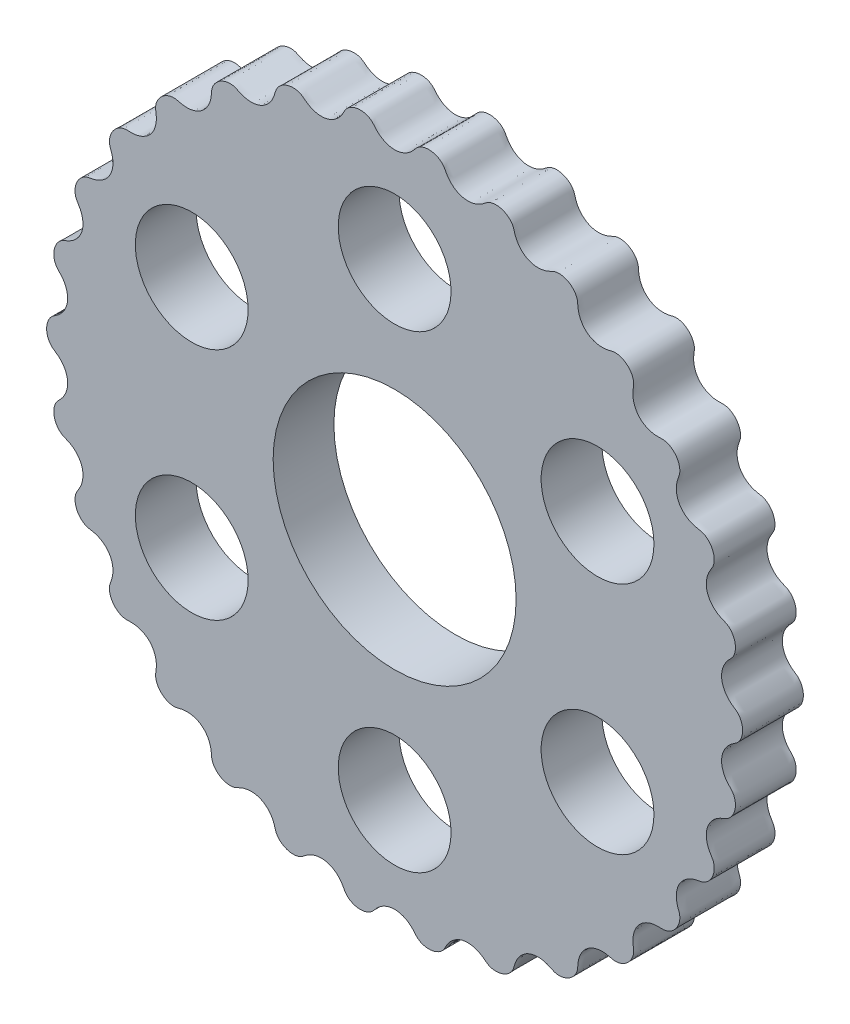
SolidWorks part; units mm, degrees
ref_plane "Front Plane" through (0, 0, 0) normal (0, 0, 1) x (1, 0, 0)
ref_plane "Top Plane" through (0, 0, 0) normal (0, 1, 0) x (1, 0, 0)
ref_plane "Right Plane" through (0, 0, 0) normal (1, 0, 0) x (0, 0, -1)
curve "Curve1"
sketch "Sketch1" plane through (0, 0, 0) normal (0, 0, 1) x (1, 0, 0)
  spline S0 degree 3 poles (1.4747, 38.2235) (0, 37.668) (-1.4747, 38.2235) (-2.1416, 38.8853) (-2.3846, 39.1801) (-2.5082, 39.3226) (-2.615, 39.4276) (-2.7406, 39.5292) (-2.9001, 39.6323) (-3.0988, 39.7306) (-3.3354, 39.8143) (-3.6035, 39.873) (-3.8933, 39.8988) (-4.1923, 39.8868) (-4.4872, 39.8364) (-4.7653, 39.7509) (-5.0154, 39.6377) (-5.2294, 39.5067) (-5.4033, 39.3692) (-5.5379, 39.2352) (-5.6396, 39.1097) (-5.7222, 38.9848) (-5.8135, 38.8197) (-5.9899, 38.4809) (-6.5047, 37.6948) (-7.8316, 36.8449) (-9.3896, 37.0816) (-10.1795, 37.5903) (-10.4785, 37.8281) (-10.6291, 37.9418) (-10.7554, 38.0223) (-10.8993, 38.0956) (-11.0767, 38.1632) (-11.2915, 38.2181) (-11.5403, 38.2508) (-11.8148, 38.2525) (-12.1036, 38.2175) (-12.3936, 38.1436) (-12.6716, 38.0329) (-12.9259, 37.8915) (-13.1469, 37.7288) (-13.329, 37.5561) (-13.4705, 37.3854) (-13.5743, 37.2264) (-13.6477, 37.0825) (-13.7025, 36.9432) (-13.7576, 36.7627) (-13.8596, 36.3946) (-14.1997, 35.5187) (-15.321, 34.4114) (-16.8941, 34.3191) (-17.7726, 34.6524) (-18.1144, 34.8229) (-18.2853, 34.9028) (-18.4256, 34.9553) (-18.5816, 34.997) (-18.7693, 35.0263) (-18.9908, 35.0353) (-19.2409, 35.0155) (-19.5098, 34.9601) (-19.785, 34.8658) (-20.0533, 34.7333) (-20.3022, 34.5672) (-20.5215, 34.376) (-20.7039, 34.1709) (-20.8461, 33.9642) (-20.949, 33.7678) (-21.0175, 33.5907) (-21.0593, 33.4347) (-21.084, 33.287) (-21.1003, 33.099) (-21.1236, 32.7177) (-21.2742, 31.7902) (-22.1407, 30.474) (-23.6602, 30.0567) (-24.5888, 30.2001) (-24.9586, 30.2957) (-25.1425, 30.3383) (-25.2906, 30.3605) (-25.4519, 30.3689) (-25.6415, 30.3585) (-25.8601, 30.3213) (-26.1006, 30.2499) (-26.3521, 30.1399) (-26.6016, 29.9904) (-26.8365, 29.8049) (-27.0455, 29.5908) (-27.2202, 29.3582) (-27.356, 29.1196) (-27.4521, 28.8878) (-27.512, 28.6743) (-27.5421, 28.4868) (-27.5506, 28.3256) (-27.544, 28.1759) (-27.5209, 27.9887) (-27.4644, 27.6109) (-27.4189, 26.6724) (-27.9928, 25.2048) (-29.3923, 24.4806) (-30.3305, 24.4278) (-30.7121, 24.4445) (-30.9007, 24.448) (-31.0502, 24.4389) (-31.2097, 24.4135) (-31.393, 24.364) (-31.5991, 24.2821) (-31.8196, 24.1623) (-32.0427, 24.0023) (-32.2557, 23.8042) (-32.4468, 23.574) (-32.6067, 23.3211) (-32.7293, 23.0572) (-32.8125, 22.7956) (-32.8583, 22.5489) (-32.8725, 22.3277) (-32.863, 22.138) (-32.8378, 21.9785) (-32.8002, 21.8335) (-32.7387, 21.6551) (-32.6049, 21.2974) (-32.3652, 20.3888) (-32.6214, 18.834) (-33.8398, 17.8346) (-34.7465, 17.588) (-35.1232, 17.5249) (-35.3085, 17.4891) (-35.4528, 17.4491) (-35.6036, 17.3912) (-35.7726, 17.3046) (-35.9571, 17.1817) (-36.1479, 17.0186) (-36.3328, 16.8158) (-36.5, 16.5777) (-36.6391, 16.3128) (-36.7429, 16.0321) (-36.808, 15.7486) (-36.8349, 15.4754) (-36.8285, 15.2246) (-36.7963, 15.0052) (-36.7476, 14.8217) (-36.6898, 14.6708) (-36.6229, 14.5368) (-36.5256, 14.3752) (-36.3204, 14.053) (-35.897, 13.2142) (-35.8244, 11.64) (-36.8084, 10.4092) (-37.644, 9.9794) (-37.9993, 9.8394) (-38.1731, 9.7659) (-38.306, 9.6967) (-38.4414, 9.6087) (-38.5887, 9.4889) (-38.7437, 9.3303) (-38.8963, 9.1312) (-39.035, 8.8943) (-39.1491, 8.6267) (-39.2301, 8.3386) (-39.2733, 8.0425) (-39.2779, 7.7516) (-39.2475, 7.4788) (-39.1891, 7.2348) (-39.112, 7.0269) (-39.0262, 6.8575) (-38.9383, 6.722) (-38.845, 6.6048) (-38.7162, 6.4669) (-38.4485, 6.1945) (-37.86, 5.462) (-37.4616, 3.9374) (-38.1683, 2.5289) (-38.8962, 1.9347) (-39.2147, 1.7239) (-39.3694, 1.6158) (-39.485, 1.5206) (-39.5991, 1.4063) (-39.7183, 1.2585) (-39.8369, 1.0712) (-39.9448, 0.8446) (-40.0313, 0.5841) (-40.0872, 0.2986) (-40.1065, 0) (-40.0872, -0.2986) (-40.0313, -0.5841) (-39.9448, -0.8446) (-39.8369, -1.0712) (-39.7183, -1.2585) (-39.5991, -1.4063) (-39.485, -1.5206) (-39.3694, -1.6158) (-39.2147, -1.7239) (-38.8962, -1.9347) (-38.1683, -2.5289) (-37.4616, -3.9374) (-37.86, -5.462) (-38.4485, -6.1945) (-38.7162, -6.4669) (-38.845, -6.6048) (-38.9383, -6.722) (-39.0262, -6.8575) (-39.112, -7.0269) (-39.1891, -7.2348) (-39.2475, -7.4788) (-39.2779, -7.7516) (-39.2733, -8.0425) (-39.2301, -8.3386) (-39.1491, -8.6267) (-39.035, -8.8943) (-38.8963, -9.1312) (-38.7437, -9.3303) (-38.5887, -9.4889) (-38.4414, -9.6087) (-38.306, -9.6967) (-38.1731, -9.7659) (-37.9993, -9.8394) (-37.644, -9.9794) (-36.8084, -10.4092) (-35.8244, -11.64) (-35.897, -13.2142) (-36.3204, -14.053) (-36.5256, -14.3752) (-36.6229, -14.5368) (-36.6898, -14.6708) (-36.7476, -14.8217) (-36.7963, -15.0052) (-36.8285, -15.2246) (-36.8349, -15.4754) (-36.808, -15.7486) (-36.7429, -16.0321) (-36.6391, -16.3128) (-36.5, -16.5777) (-36.3328, -16.8158) (-36.1479, -17.0186) (-35.9571, -17.1817) (-35.7726, -17.3046) (-35.6036, -17.3912) (-35.4528, -17.4491) (-35.3085, -17.4891) (-35.1232, -17.5249) (-34.7465, -17.588) (-33.8398, -17.8346) (-32.6214, -18.834) (-32.3652, -20.3888) (-32.6049, -21.2974) (-32.7387, -21.6551) (-32.8002, -21.8335) (-32.8378, -21.9785) (-32.863, -22.138) (-32.8725, -22.3277) (-32.8583, -22.5489) (-32.8125, -22.7956) (-32.7293, -23.0572) (-32.6067, -23.3211) (-32.4468, -23.574) (-32.2557, -23.8042) (-32.0427, -24.0023) (-31.8196, -24.1623) (-31.5991, -24.2821) (-31.393, -24.364) (-31.2097, -24.4135) (-31.0502, -24.4389) (-30.9007, -24.448) (-30.7121, -24.4445) (-30.3305, -24.4278) (-29.3923, -24.4806) (-27.9928, -25.2048) (-27.4189, -26.6724) (-27.4644, -27.6109) (-27.5209, -27.9887) (-27.544, -28.1759) (-27.5506, -28.3256) (-27.5421, -28.4868) (-27.512, -28.6743) (-27.4521, -28.8878) (-27.356, -29.1196) (-27.2202, -29.3582) (-27.0455, -29.5908) (-26.8365, -29.8049) (-26.6016, -29.9904) (-26.3521, -30.1399) (-26.1006, -30.2499) (-25.8601, -30.3213) (-25.6415, -30.3585) (-25.4519, -30.3689) (-25.2906, -30.3605) (-25.1425, -30.3383) (-24.9586, -30.2957) (-24.5888, -30.2001) (-23.6602, -30.0567) (-22.1407, -30.474) (-21.2742, -31.7902) (-21.1236, -32.7177) (-21.1003, -33.099) (-21.084, -33.287) (-21.0593, -33.4347) (-21.0175, -33.5907) (-20.949, -33.7678) (-20.8461, -33.9642) (-20.7039, -34.1709) (-20.5215, -34.376) (-20.3022, -34.5672) (-20.0533, -34.7333) (-19.785, -34.8658) (-19.5098, -34.9601) (-19.2409, -35.0155) (-18.9908, -35.0353) (-18.7693, -35.0263) (-18.5816, -34.997) (-18.4256, -34.9553) (-18.2853, -34.9028) (-18.1144, -34.8229) (-17.7726, -34.6524) (-16.8941, -34.3191) (-15.321, -34.4114) (-14.1997, -35.5187) (-13.8596, -36.3946) (-13.7576, -36.7627) (-13.7025, -36.9432) (-13.6477, -37.0825) (-13.5743, -37.2264) (-13.4705, -37.3854) (-13.329, -37.5561) (-13.1469, -37.7288) (-12.9259, -37.8915) (-12.6716, -38.0329) (-12.3936, -38.1436) (-12.1036, -38.2175) (-11.8148, -38.2525) (-11.5403, -38.2508) (-11.2915, -38.2181) (-11.0767, -38.1632) (-10.8993, -38.0956) (-10.7554, -38.0223) (-10.6291, -37.9418) (-10.4785, -37.8281) (-10.1795, -37.5903) (-9.3896, -37.0816) (-7.8316, -36.8449) (-6.5047, -37.6948) (-5.9899, -38.4809) (-5.8135, -38.8197) (-5.7222, -38.9848) (-5.6396, -39.1097) (-5.5379, -39.2352) (-5.4033, -39.3692) (-5.2294, -39.5067) (-5.0154, -39.6377) (-4.7653, -39.7509) (-4.4872, -39.8364) (-4.1923, -39.8868) (-3.8933, -39.8988) (-3.6035, -39.873) (-3.3354, -39.8143) (-3.0988, -39.7306) (-2.9001, -39.6323) (-2.7406, -39.5292) (-2.615, -39.4276) (-2.5082, -39.3226) (-2.3846, -39.1801) (-2.1416, -38.8853) (-1.4747, -38.2235) (0, -37.668) (1.4747, -38.2235) (2.1416, -38.8853) (2.3846, -39.1801) (2.5082, -39.3226) (2.615, -39.4276) (2.7406, -39.5292) (2.9001, -39.6323) (3.0988, -39.7306) (3.3354, -39.8143) (3.6035, -39.873) (3.8933, -39.8988) (4.1923, -39.8868) (4.4872, -39.8364) (4.7653, -39.7509) (5.0154, -39.6377) (5.2294, -39.5067) (5.4033, -39.3692) (5.5379, -39.2352) (5.6396, -39.1097) (5.7222, -38.9848) (5.8135, -38.8197) (5.9899, -38.4809) (6.5047, -37.6948) (7.8316, -36.8449) (9.3896, -37.0816) (10.1795, -37.5903) (10.4785, -37.8281) (10.6291, -37.9418) (10.7554, -38.0223) (10.8993, -38.0956) (11.0767, -38.1632) (11.2915, -38.2181) (11.5403, -38.2508) (11.8148, -38.2525) (12.1036, -38.2175) (12.3936, -38.1436) (12.6716, -38.0329) (12.9259, -37.8915) (13.1469, -37.7288) (13.329, -37.5561) (13.4705, -37.3854) (13.5743, -37.2264) (13.6477, -37.0825) (13.7025, -36.9432) (13.7576, -36.7627) (13.8596, -36.3946) (14.1997, -35.5187) (15.321, -34.4114) (16.8941, -34.3191) (17.7726, -34.6524) (18.1144, -34.8229) (18.2853, -34.9028) (18.4256, -34.9553) (18.5816, -34.997) (18.7693, -35.0263) (18.9908, -35.0353) (19.2409, -35.0155) (19.5098, -34.9601) (19.785, -34.8658) (20.0533, -34.7333) (20.3022, -34.5672) (20.5215, -34.376) (20.7039, -34.1709) (20.8461, -33.9642) (20.949, -33.7678) (21.0175, -33.5907) (21.0593, -33.4347) (21.084, -33.287) (21.1003, -33.099) (21.1236, -32.7177) (21.2742, -31.7902) (22.1407, -30.474) (23.6602, -30.0567) (24.5888, -30.2001) (24.9586, -30.2957) (25.1425, -30.3383) (25.2906, -30.3605) (25.4519, -30.3689) (25.6415, -30.3585) (25.8601, -30.3213) (26.1006, -30.2499) (26.3521, -30.1399) (26.6016, -29.9904) (26.8365, -29.8049) (27.0455, -29.5908) (27.2202, -29.3582) (27.356, -29.1196) (27.4521, -28.8878) (27.512, -28.6743) (27.5421, -28.4868) (27.5506, -28.3256) (27.544, -28.1759) (27.5209, -27.9887) (27.4644, -27.6109) (27.4189, -26.6724) (27.9928, -25.2048) (29.3923, -24.4806) (30.3305, -24.4278) (30.7121, -24.4445) (30.9007, -24.448) (31.0502, -24.4389) (31.2097, -24.4135) (31.393, -24.364) (31.5991, -24.2821) (31.8196, -24.1623) (32.0427, -24.0023) (32.2557, -23.8042) (32.4468, -23.574) (32.6067, -23.3211) (32.7293, -23.0572) (32.8125, -22.7956) (32.8583, -22.5489) (32.8725, -22.3277) (32.863, -22.138) (32.8378, -21.9785) (32.8002, -21.8335) (32.7387, -21.6551) (32.6049, -21.2974) (32.3652, -20.3888) (32.6214, -18.834) (33.8398, -17.8346) (34.7465, -17.588) (35.1232, -17.5249) (35.3085, -17.4891) (35.4528, -17.4491) (35.6036, -17.3912) (35.7726, -17.3046) (35.9571, -17.1817) (36.1479, -17.0186) (36.3328, -16.8158) (36.5, -16.5777) (36.6391, -16.3128) (36.7429, -16.0321) (36.808, -15.7486) (36.8349, -15.4754) (36.8285, -15.2246) (36.7963, -15.0052) (36.7476, -14.8217) (36.6898, -14.6708) (36.6229, -14.5368) (36.5256, -14.3752) (36.3204, -14.053) (35.897, -13.2142) (35.8244, -11.64) (36.8084, -10.4092) (37.644, -9.9794) (37.9993, -9.8394) (38.1731, -9.7659) (38.306, -9.6967) (38.4414, -9.6087) (38.5887, -9.4889) (38.7437, -9.3303) (38.8963, -9.1312) (39.035, -8.8943) (39.1491, -8.6267) (39.2301, -8.3386) (39.2733, -8.0425) (39.2779, -7.7516) (39.2475, -7.4788) (39.1891, -7.2348) (39.112, -7.0269) (39.0262, -6.8575) (38.9383, -6.722) (38.845, -6.6048) (38.7162, -6.4669) (38.4485, -6.1945) (37.86, -5.462) (37.4616, -3.9374) (38.1683, -2.5289) (38.8962, -1.9347) (39.2147, -1.7239) (39.3694, -1.6158) (39.485, -1.5206) (39.5991, -1.4063) (39.7183, -1.2585) (39.8369, -1.0712) (39.9448, -0.8446) (40.0313, -0.5841) (40.0872, -0.2986) (40.1065, 0) (40.0872, 0.2986) (40.0313, 0.5841) (39.9448, 0.8446) (39.8369, 1.0712) (39.7183, 1.2585) (39.5991, 1.4063) (39.485, 1.5206) (39.3694, 1.6158) (39.2147, 1.7239) (38.8962, 1.9347) (38.1683, 2.5289) (37.4616, 3.9374) (37.86, 5.462) (38.4485, 6.1945) (38.7162, 6.4669) (38.845, 6.6048) (38.9383, 6.722) (39.0262, 6.8575) (39.112, 7.0269) (39.1891, 7.2348) (39.2475, 7.4788) (39.2779, 7.7516) (39.2733, 8.0425) (39.2301, 8.3386) (39.1491, 8.6267) (39.035, 8.8943) (38.8963, 9.1312) (38.7437, 9.3303) (38.5887, 9.4889) (38.4414, 9.6087) (38.306, 9.6967) (38.1731, 9.7659) (37.9993, 9.8394) (37.644, 9.9794) (36.8084, 10.4092) (35.8244, 11.64) (35.897, 13.2142) (36.3204, 14.053) (36.5256, 14.3752) (36.6229, 14.5368) (36.6898, 14.6708) (36.7476, 14.8217) (36.7963, 15.0052) (36.8285, 15.2246) (36.8349, 15.4754) (36.808, 15.7486) (36.7429, 16.0321) (36.6391, 16.3128) (36.5, 16.5777) (36.3328, 16.8158) (36.1479, 17.0186) (35.9571, 17.1817) (35.7726, 17.3046) (35.6036, 17.3912) (35.4528, 17.4491) (35.3085, 17.4891) (35.1232, 17.5249) (34.7465, 17.588) (33.8398, 17.8346) (32.6214, 18.834) (32.3652, 20.3888) (32.6049, 21.2974) (32.7387, 21.6551) (32.8002, 21.8335) (32.8378, 21.9785) (32.863, 22.138) (32.8725, 22.3277) (32.8583, 22.5489) (32.8125, 22.7956) (32.7293, 23.0572) (32.6067, 23.3211) (32.4468, 23.574) (32.2557, 23.8042) (32.0427, 24.0023) (31.8196, 24.1623) (31.5991, 24.2821) (31.393, 24.364) (31.2097, 24.4135) (31.0502, 24.4389) (30.9007, 24.448) (30.7121, 24.4445) (30.3305, 24.4278) (29.3923, 24.4806) (27.9928, 25.2048) (27.4189, 26.6724) (27.4644, 27.6109) (27.5209, 27.9887) (27.544, 28.1759) (27.5506, 28.3256) (27.5421, 28.4868) (27.512, 28.6743) (27.4521, 28.8878) (27.356, 29.1196) (27.2202, 29.3582) (27.0455, 29.5908) (26.8365, 29.8049) (26.6016, 29.9904) (26.3521, 30.1399) (26.1006, 30.2499) (25.8601, 30.3213) (25.6415, 30.3585) (25.4519, 30.3689) (25.2906, 30.3605) (25.1425, 30.3383) (24.9586, 30.2957) (24.5888, 30.2001) (23.6602, 30.0567) (22.1407, 30.474) (21.2742, 31.7902) (21.1236, 32.7177) (21.1003, 33.099) (21.084, 33.287) (21.0593, 33.4347) (21.0175, 33.5907) (20.949, 33.7678) (20.8461, 33.9642) (20.7039, 34.1709) (20.5215, 34.376) (20.3022, 34.5672) (20.0533, 34.7333) (19.785, 34.8658) (19.5098, 34.9601) (19.2409, 35.0155) (18.9908, 35.0353) (18.7693, 35.0263) (18.5816, 34.997) (18.4256, 34.9553) (18.2853, 34.9028) (18.1144, 34.8229) (17.7726, 34.6524) (16.8941, 34.3191) (15.321, 34.4114) (14.1997, 35.5187) (13.8596, 36.3946) (13.7576, 36.7627) (13.7025, 36.9432) (13.6477, 37.0825) (13.5743, 37.2264) (13.4705, 37.3854) (13.329, 37.5561) (13.1469, 37.7288) (12.9259, 37.8915) (12.6716, 38.0329) (12.3936, 38.1436) (12.1036, 38.2175) (11.8148, 38.2525) (11.5403, 38.2508) (11.2915, 38.2181) (11.0767, 38.1632) (10.8993, 38.0956) (10.7554, 38.0223) (10.6291, 37.9418) (10.4785, 37.8281) (10.1795, 37.5903) (9.3896, 37.0816) (7.8316, 36.8449) (6.5047, 37.6948) (5.9899, 38.4809) (5.8135, 38.8197) (5.7222, 38.9848) (5.6396, 39.1097) (5.5379, 39.2352) (5.4033, 39.3692) (5.2294, 39.5067) (5.0154, 39.6377) (4.7653, 39.7509) (4.4872, 39.8364) (4.1923, 39.8868) (3.8933, 39.8988) (3.6035, 39.873) (3.3354, 39.8143) (3.0988, 39.7306) (2.9001, 39.6323) (2.7406, 39.5292) (2.615, 39.4276) (2.5082, 39.3226) (2.3846, 39.1801) (2.1416, 38.8853) (1.4747, 38.2235) (0, 37.668) (-1.4747, 38.2235) knots -0.009773 -0.008819 -0.006325 0 0.006325 0.008819 0.009773 0.010309 0.010787 0.011333 0.01199 0.012763 0.013641 0.014601 0.015619 0.016667 0.017714 0.018732 0.019693 0.02057 0.021343 0.022 0.022547 0.023025 0.02356 0.024514 0.027009 0.033333 0.039658 0.042152 0.043106 0.043642 0.04412 0.044667 0.045324 0.046097 0.046974 0.047935 0.048953 0.05 0.051047 0.052065 0.053026 0.053903 0.054676 0.055333 0.05588 0.056358 0.056894 0.057848 0.060342 0.066667 0.072991 0.075486 0.07644 0.076975 0.077453 0.078 0.078657 0.07943 0.080307 0.081268 0.082286 0.083333 0.084381 0.085399 0.086359 0.087237 0.08801 0.088667 0.089213 0.089691 0.090227 0.091181 0.093675 0.1 0.106325 0.108819 0.109773 0.110309 0.110787 0.111333 0.11199 0.112763 0.113641 0.114601 0.115619 0.116667 0.117714 0.118732 0.119693 0.12057 0.121343 0.122 0.122547 0.123025 0.12356 0.124514 0.127009 0.133333 0.139658 0.142152 0.143106 0.143642 0.14412 0.144667 0.145324 0.146097 0.146974 0.147935 0.148953 0.15 0.151047 0.152065 0.153026 0.153903 0.154676 0.155333 0.15588 0.156358 0.156894 0.157848 0.160342 0.166667 0.172991 0.175486 0.17644 0.176975 0.177453 0.178 0.178657 0.17943 0.180307 0.181268 0.182286 0.183333 0.184381 0.185399 0.186359 0.187237 0.18801 0.188667 0.189213 0.189691 0.190227 0.191181 0.193675 0.2 0.206325 0.208819 0.209773 0.210309 0.210787 0.211333 0.21199 0.212763 0.213641 0.214601 0.215619 0.216667 0.217714 0.218732 0.219693 0.22057 0.221343 0.222 0.222547 0.223025 0.22356 0.224514 0.227009 0.233333 0.239658 0.242152 0.243106 0.243642 0.24412 0.244667 0.245324 0.246097 0.246974 0.247935 0.248953 0.25 0.251047 0.252065 0.253026 0.253903 0.254676 0.255333 0.25588 0.256358 0.256894 0.257848 0.260342 0.266667 0.272991 0.275486 0.27644 0.276975 0.277453 0.278 0.278657 0.27943 0.280307 0.281268 0.282286 0.283333 0.284381 0.285399 0.286359 0.287237 0.28801 0.288667 0.289213 0.289691 0.290227 0.291181 0.293675 0.3 0.306325 0.308819 0.309773 0.310309 0.310787 0.311333 0.31199 0.312763 0.313641 0.314601 0.315619 0.316667 0.317714 0.318732 0.319693 0.32057 0.321343 0.322 0.322547 0.323025 0.32356 0.324514 0.327009 0.333333 0.339658 0.342152 0.343106 0.343642 0.34412 0.344667 0.345324 0.346097 0.346974 0.347935 0.348953 0.35 0.351047 0.352065 0.353026 0.353903 0.354676 0.355333 0.35588 0.356358 0.356894 0.357848 0.360342 0.366667 0.372991 0.375486 0.37644 0.376975 0.377453 0.378 0.378657 0.37943 0.380307 0.381268 0.382286 0.383333 0.384381 0.385399 0.386359 0.387237 0.38801 0.388667 0.389213 0.389691 0.390227 0.391181 0.393675 0.4 0.406325 0.408819 0.409773 0.410309 0.410787 0.411333 0.41199 0.412763 0.413641 0.414601 0.415619 0.416667 0.417714 0.418732 0.419693 0.42057 0.421343 0.422 0.422547 0.423025 0.42356 0.424514 0.427009 0.433333 0.439658 0.442152 0.443106 0.443642 0.44412 0.444667 0.445324 0.446097 0.446974 0.447935 0.448953 0.45 0.451047 0.452065 0.453026 0.453903 0.454676 0.455333 0.45588 0.456358 0.456894 0.457848 0.460342 0.466667 0.472991 0.475486 0.47644 0.476975 0.477453 0.478 0.478657 0.47943 0.480307 0.481268 0.482286 0.483333 0.484381 0.485399 0.486359 0.487237 0.48801 0.488667 0.489213 0.489691 0.490227 0.491181 0.493675 0.5 0.506325 0.508819 0.509773 0.510309 0.510787 0.511333 0.51199 0.512763 0.513641 0.514601 0.515619 0.516667 0.517714 0.518732 0.519693 0.52057 0.521343 0.522 0.522547 0.523025 0.52356 0.524514 0.527009 0.533333 0.539658 0.542152 0.543106 0.543642 0.54412 0.544667 0.545324 0.546097 0.546974 0.547935 0.548953 0.55 0.551047 0.552065 0.553026 0.553903 0.554676 0.555333 0.55588 0.556358 0.556894 0.557848 0.560342 0.566667 0.572991 0.575486 0.57644 0.576975 0.577453 0.578 0.578657 0.57943 0.580307 0.581268 0.582286 0.583333 0.584381 0.585399 0.586359 0.587237 0.58801 0.588667 0.589213 0.589691 0.590227 0.591181 0.593675 0.6 0.606325 0.608819 0.609773 0.610309 0.610787 0.611333 0.61199 0.612763 0.613641 0.614601 0.615619 0.616667 0.617714 0.618732 0.619693 0.62057 0.621343 0.622 0.622547 0.623025 0.62356 0.624514 0.627009 0.633333 0.639658 0.642152 0.643106 0.643642 0.64412 0.644667 0.645324 0.646097 0.646974 0.647935 0.648953 0.65 0.651047 0.652065 0.653026 0.653903 0.654676 0.655333 0.65588 0.656358 0.656894 0.657848 0.660342 0.666667 0.672991 0.675486 0.67644 0.676975 0.677453 0.678 0.678657 0.67943 0.680307 0.681268 0.682286 0.683333 0.684381 0.685399 0.686359 0.687237 0.68801 0.688667 0.689213 0.689691 0.690227 0.691181 0.693675 0.7 0.706325 0.708819 0.709773 0.710309 0.710787 0.711333 0.71199 0.712763 0.713641 0.714601 0.715619 0.716667 0.717714 0.718732 0.719693 0.72057 0.721343 0.722 0.722547 0.723025 0.72356 0.724514 0.727009 0.733333 0.739658 0.742152 0.743106 0.743642 0.74412 0.744667 0.745324 0.746097 0.746974 0.747935 0.748953 0.75 0.751047 0.752065 0.753026 0.753903 0.754676 0.755333 0.75588 0.756358 0.756894 0.757848 0.760342 0.766667 0.772991 0.775486 0.77644 0.776975 0.777453 0.778 0.778657 0.77943 0.780307 0.781268 0.782286 0.783333 0.784381 0.785399 0.786359 0.787237 0.78801 0.788667 0.789213 0.789691 0.790227 0.791181 0.793675 0.8 0.806325 0.808819 0.809773 0.810309 0.810787 0.811333 0.81199 0.812763 0.813641 0.814601 0.815619 0.816667 0.817714 0.818732 0.819693 0.82057 0.821343 0.822 0.822547 0.823025 0.82356 0.824514 0.827009 0.833333 0.839658 0.842152 0.843106 0.843642 0.84412 0.844667 0.845324 0.846097 0.846974 0.847935 0.848953 0.85 0.851047 0.852065 0.853026 0.853903 0.854676 0.855333 0.85588 0.856358 0.856894 0.857848 0.860342 0.866667 0.872991 0.875486 0.87644 0.876975 0.877453 0.878 0.878657 0.87943 0.880307 0.881268 0.882286 0.883333 0.884381 0.885399 0.886359 0.887237 0.88801 0.888667 0.889213 0.889691 0.890227 0.891181 0.893675 0.9 0.906325 0.908819 0.909773 0.910309 0.910787 0.911333 0.91199 0.912763 0.913641 0.914601 0.915619 0.916667 0.917714 0.918732 0.919693 0.92057 0.921343 0.922 0.922547 0.923025 0.92356 0.924514 0.927009 0.933333 0.939658 0.942152 0.943106 0.943642 0.94412 0.944667 0.945324 0.946097 0.946974 0.947935 0.948953 0.95 0.951047 0.952065 0.953026 0.953903 0.954676 0.955333 0.95588 0.956358 0.956894 0.957848 0.960342 0.966667 0.972991 0.975486 0.97644 0.976975 0.977453 0.978 0.978657 0.97943 0.980307 0.981268 0.982286 0.983333 0.984381 0.985399 0.986359 0.987237 0.98801 0.988667 0.989213 0.989691 0.990227 0.991181 0.993675 1 1.006325 1.008819 1.009773 only from (0, 37.9) to (0, 37.9) construction
  spline S1 degree 3 poles (1.4747, 38.2235) (0, 37.668) (-1.4747, 38.2235) (-2.1416, 38.8853) (-2.3846, 39.1801) (-2.5082, 39.3226) (-2.615, 39.4276) (-2.7406, 39.5292) (-2.9001, 39.6323) (-3.0988, 39.7306) (-3.3354, 39.8143) (-3.6035, 39.873) (-3.8933, 39.8988) (-4.1923, 39.8868) (-4.4872, 39.8364) (-4.7653, 39.7509) (-5.0154, 39.6377) (-5.2294, 39.5067) (-5.4033, 39.3692) (-5.5379, 39.2352) (-5.6396, 39.1097) (-5.7222, 38.9848) (-5.8135, 38.8197) (-5.9899, 38.4809) (-6.5047, 37.6948) (-7.8316, 36.8449) (-9.3896, 37.0816) (-10.1795, 37.5903) (-10.4785, 37.8281) (-10.6291, 37.9418) (-10.7554, 38.0223) (-10.8993, 38.0956) (-11.0767, 38.1632) (-11.2915, 38.2181) (-11.5403, 38.2508) (-11.8148, 38.2525) (-12.1036, 38.2175) (-12.3936, 38.1436) (-12.6716, 38.0329) (-12.9259, 37.8915) (-13.1469, 37.7288) (-13.329, 37.5561) (-13.4705, 37.3854) (-13.5743, 37.2264) (-13.6477, 37.0825) (-13.7025, 36.9432) (-13.7576, 36.7627) (-13.8596, 36.3946) (-14.1997, 35.5187) (-15.321, 34.4114) (-16.8941, 34.3191) (-17.7726, 34.6524) (-18.1144, 34.8229) (-18.2853, 34.9028) (-18.4256, 34.9553) (-18.5816, 34.997) (-18.7693, 35.0263) (-18.9908, 35.0353) (-19.2409, 35.0155) (-19.5098, 34.9601) (-19.785, 34.8658) (-20.0533, 34.7333) (-20.3022, 34.5672) (-20.5215, 34.376) (-20.7039, 34.1709) (-20.8461, 33.9642) (-20.949, 33.7678) (-21.0175, 33.5907) (-21.0593, 33.4347) (-21.084, 33.287) (-21.1003, 33.099) (-21.1236, 32.7177) (-21.2742, 31.7902) (-22.1407, 30.474) (-23.6602, 30.0567) (-24.5888, 30.2001) (-24.9586, 30.2957) (-25.1425, 30.3383) (-25.2906, 30.3605) (-25.4519, 30.3689) (-25.6415, 30.3585) (-25.8601, 30.3213) (-26.1006, 30.2499) (-26.3521, 30.1399) (-26.6016, 29.9904) (-26.8365, 29.8049) (-27.0455, 29.5908) (-27.2202, 29.3582) (-27.356, 29.1196) (-27.4521, 28.8878) (-27.512, 28.6743) (-27.5421, 28.4868) (-27.5506, 28.3256) (-27.544, 28.1759) (-27.5209, 27.9887) (-27.4644, 27.6109) (-27.4189, 26.6724) (-27.9928, 25.2048) (-29.3923, 24.4806) (-30.3305, 24.4278) (-30.7121, 24.4445) (-30.9007, 24.448) (-31.0502, 24.4389) (-31.2097, 24.4135) (-31.393, 24.364) (-31.5991, 24.2821) (-31.8196, 24.1623) (-32.0427, 24.0023) (-32.2557, 23.8042) (-32.4468, 23.574) (-32.6067, 23.3211) (-32.7293, 23.0572) (-32.8125, 22.7956) (-32.8583, 22.5489) (-32.8725, 22.3277) (-32.863, 22.138) (-32.8378, 21.9785) (-32.8002, 21.8335) (-32.7387, 21.6551) (-32.6049, 21.2974) (-32.3652, 20.3888) (-32.6214, 18.834) (-33.8398, 17.8346) (-34.7465, 17.588) (-35.1232, 17.5249) (-35.3085, 17.4891) (-35.4528, 17.4491) (-35.6036, 17.3912) (-35.7726, 17.3046) (-35.9571, 17.1817) (-36.1479, 17.0186) (-36.3328, 16.8158) (-36.5, 16.5777) (-36.6391, 16.3128) (-36.7429, 16.0321) (-36.808, 15.7486) (-36.8349, 15.4754) (-36.8285, 15.2246) (-36.7963, 15.0052) (-36.7476, 14.8217) (-36.6898, 14.6708) (-36.6229, 14.5368) (-36.5256, 14.3752) (-36.3204, 14.053) (-35.897, 13.2142) (-35.8244, 11.64) (-36.8084, 10.4092) (-37.644, 9.9794) (-37.9993, 9.8394) (-38.1731, 9.7659) (-38.306, 9.6967) (-38.4414, 9.6087) (-38.5887, 9.4889) (-38.7437, 9.3303) (-38.8963, 9.1312) (-39.035, 8.8943) (-39.1491, 8.6267) (-39.2301, 8.3386) (-39.2733, 8.0425) (-39.2779, 7.7516) (-39.2475, 7.4788) (-39.1891, 7.2348) (-39.112, 7.0269) (-39.0262, 6.8575) (-38.9383, 6.722) (-38.845, 6.6048) (-38.7162, 6.4669) (-38.4485, 6.1945) (-37.86, 5.462) (-37.4616, 3.9374) (-38.1683, 2.5289) (-38.8962, 1.9347) (-39.2147, 1.7239) (-39.3694, 1.6158) (-39.485, 1.5206) (-39.5991, 1.4063) (-39.7183, 1.2585) (-39.8369, 1.0712) (-39.9448, 0.8446) (-40.0313, 0.5841) (-40.0872, 0.2986) (-40.1065, 0) (-40.0872, -0.2986) (-40.0313, -0.5841) (-39.9448, -0.8446) (-39.8369, -1.0712) (-39.7183, -1.2585) (-39.5991, -1.4063) (-39.485, -1.5206) (-39.3694, -1.6158) (-39.2147, -1.7239) (-38.8962, -1.9347) (-38.1683, -2.5289) (-37.4616, -3.9374) (-37.86, -5.462) (-38.4485, -6.1945) (-38.7162, -6.4669) (-38.845, -6.6048) (-38.9383, -6.722) (-39.0262, -6.8575) (-39.112, -7.0269) (-39.1891, -7.2348) (-39.2475, -7.4788) (-39.2779, -7.7516) (-39.2733, -8.0425) (-39.2301, -8.3386) (-39.1491, -8.6267) (-39.035, -8.8943) (-38.8963, -9.1312) (-38.7437, -9.3303) (-38.5887, -9.4889) (-38.4414, -9.6087) (-38.306, -9.6967) (-38.1731, -9.7659) (-37.9993, -9.8394) (-37.644, -9.9794) (-36.8084, -10.4092) (-35.8244, -11.64) (-35.897, -13.2142) (-36.3204, -14.053) (-36.5256, -14.3752) (-36.6229, -14.5368) (-36.6898, -14.6708) (-36.7476, -14.8217) (-36.7963, -15.0052) (-36.8285, -15.2246) (-36.8349, -15.4754) (-36.808, -15.7486) (-36.7429, -16.0321) (-36.6391, -16.3128) (-36.5, -16.5777) (-36.3328, -16.8158) (-36.1479, -17.0186) (-35.9571, -17.1817) (-35.7726, -17.3046) (-35.6036, -17.3912) (-35.4528, -17.4491) (-35.3085, -17.4891) (-35.1232, -17.5249) (-34.7465, -17.588) (-33.8398, -17.8346) (-32.6214, -18.834) (-32.3652, -20.3888) (-32.6049, -21.2974) (-32.7387, -21.6551) (-32.8002, -21.8335) (-32.8378, -21.9785) (-32.863, -22.138) (-32.8725, -22.3277) (-32.8583, -22.5489) (-32.8125, -22.7956) (-32.7293, -23.0572) (-32.6067, -23.3211) (-32.4468, -23.574) (-32.2557, -23.8042) (-32.0427, -24.0023) (-31.8196, -24.1623) (-31.5991, -24.2821) (-31.393, -24.364) (-31.2097, -24.4135) (-31.0502, -24.4389) (-30.9007, -24.448) (-30.7121, -24.4445) (-30.3305, -24.4278) (-29.3923, -24.4806) (-27.9928, -25.2048) (-27.4189, -26.6724) (-27.4644, -27.6109) (-27.5209, -27.9887) (-27.544, -28.1759) (-27.5506, -28.3256) (-27.5421, -28.4868) (-27.512, -28.6743) (-27.4521, -28.8878) (-27.356, -29.1196) (-27.2202, -29.3582) (-27.0455, -29.5908) (-26.8365, -29.8049) (-26.6016, -29.9904) (-26.3521, -30.1399) (-26.1006, -30.2499) (-25.8601, -30.3213) (-25.6415, -30.3585) (-25.4519, -30.3689) (-25.2906, -30.3605) (-25.1425, -30.3383) (-24.9586, -30.2957) (-24.5888, -30.2001) (-23.6602, -30.0567) (-22.1407, -30.474) (-21.2742, -31.7902) (-21.1236, -32.7177) (-21.1003, -33.099) (-21.084, -33.287) (-21.0593, -33.4347) (-21.0175, -33.5907) (-20.949, -33.7678) (-20.8461, -33.9642) (-20.7039, -34.1709) (-20.5215, -34.376) (-20.3022, -34.5672) (-20.0533, -34.7333) (-19.785, -34.8658) (-19.5098, -34.9601) (-19.2409, -35.0155) (-18.9908, -35.0353) (-18.7693, -35.0263) (-18.5816, -34.997) (-18.4256, -34.9553) (-18.2853, -34.9028) (-18.1144, -34.8229) (-17.7726, -34.6524) (-16.8941, -34.3191) (-15.321, -34.4114) (-14.1997, -35.5187) (-13.8596, -36.3946) (-13.7576, -36.7627) (-13.7025, -36.9432) (-13.6477, -37.0825) (-13.5743, -37.2264) (-13.4705, -37.3854) (-13.329, -37.5561) (-13.1469, -37.7288) (-12.9259, -37.8915) (-12.6716, -38.0329) (-12.3936, -38.1436) (-12.1036, -38.2175) (-11.8148, -38.2525) (-11.5403, -38.2508) (-11.2915, -38.2181) (-11.0767, -38.1632) (-10.8993, -38.0956) (-10.7554, -38.0223) (-10.6291, -37.9418) (-10.4785, -37.8281) (-10.1795, -37.5903) (-9.3896, -37.0816) (-7.8316, -36.8449) (-6.5047, -37.6948) (-5.9899, -38.4809) (-5.8135, -38.8197) (-5.7222, -38.9848) (-5.6396, -39.1097) (-5.5379, -39.2352) (-5.4033, -39.3692) (-5.2294, -39.5067) (-5.0154, -39.6377) (-4.7653, -39.7509) (-4.4872, -39.8364) (-4.1923, -39.8868) (-3.8933, -39.8988) (-3.6035, -39.873) (-3.3354, -39.8143) (-3.0988, -39.7306) (-2.9001, -39.6323) (-2.7406, -39.5292) (-2.615, -39.4276) (-2.5082, -39.3226) (-2.3846, -39.1801) (-2.1416, -38.8853) (-1.4747, -38.2235) (0, -37.668) (1.4747, -38.2235) (2.1416, -38.8853) (2.3846, -39.1801) (2.5082, -39.3226) (2.615, -39.4276) (2.7406, -39.5292) (2.9001, -39.6323) (3.0988, -39.7306) (3.3354, -39.8143) (3.6035, -39.873) (3.8933, -39.8988) (4.1923, -39.8868) (4.4872, -39.8364) (4.7653, -39.7509) (5.0154, -39.6377) (5.2294, -39.5067) (5.4033, -39.3692) (5.5379, -39.2352) (5.6396, -39.1097) (5.7222, -38.9848) (5.8135, -38.8197) (5.9899, -38.4809) (6.5047, -37.6948) (7.8316, -36.8449) (9.3896, -37.0816) (10.1795, -37.5903) (10.4785, -37.8281) (10.6291, -37.9418) (10.7554, -38.0223) (10.8993, -38.0956) (11.0767, -38.1632) (11.2915, -38.2181) (11.5403, -38.2508) (11.8148, -38.2525) (12.1036, -38.2175) (12.3936, -38.1436) (12.6716, -38.0329) (12.9259, -37.8915) (13.1469, -37.7288) (13.329, -37.5561) (13.4705, -37.3854) (13.5743, -37.2264) (13.6477, -37.0825) (13.7025, -36.9432) (13.7576, -36.7627) (13.8596, -36.3946) (14.1997, -35.5187) (15.321, -34.4114) (16.8941, -34.3191) (17.7726, -34.6524) (18.1144, -34.8229) (18.2853, -34.9028) (18.4256, -34.9553) (18.5816, -34.997) (18.7693, -35.0263) (18.9908, -35.0353) (19.2409, -35.0155) (19.5098, -34.9601) (19.785, -34.8658) (20.0533, -34.7333) (20.3022, -34.5672) (20.5215, -34.376) (20.7039, -34.1709) (20.8461, -33.9642) (20.949, -33.7678) (21.0175, -33.5907) (21.0593, -33.4347) (21.084, -33.287) (21.1003, -33.099) (21.1236, -32.7177) (21.2742, -31.7902) (22.1407, -30.474) (23.6602, -30.0567) (24.5888, -30.2001) (24.9586, -30.2957) (25.1425, -30.3383) (25.2906, -30.3605) (25.4519, -30.3689) (25.6415, -30.3585) (25.8601, -30.3213) (26.1006, -30.2499) (26.3521, -30.1399) (26.6016, -29.9904) (26.8365, -29.8049) (27.0455, -29.5908) (27.2202, -29.3582) (27.356, -29.1196) (27.4521, -28.8878) (27.512, -28.6743) (27.5421, -28.4868) (27.5506, -28.3256) (27.544, -28.1759) (27.5209, -27.9887) (27.4644, -27.6109) (27.4189, -26.6724) (27.9928, -25.2048) (29.3923, -24.4806) (30.3305, -24.4278) (30.7121, -24.4445) (30.9007, -24.448) (31.0502, -24.4389) (31.2097, -24.4135) (31.393, -24.364) (31.5991, -24.2821) (31.8196, -24.1623) (32.0427, -24.0023) (32.2557, -23.8042) (32.4468, -23.574) (32.6067, -23.3211) (32.7293, -23.0572) (32.8125, -22.7956) (32.8583, -22.5489) (32.8725, -22.3277) (32.863, -22.138) (32.8378, -21.9785) (32.8002, -21.8335) (32.7387, -21.6551) (32.6049, -21.2974) (32.3652, -20.3888) (32.6214, -18.834) (33.8398, -17.8346) (34.7465, -17.588) (35.1232, -17.5249) (35.3085, -17.4891) (35.4528, -17.4491) (35.6036, -17.3912) (35.7726, -17.3046) (35.9571, -17.1817) (36.1479, -17.0186) (36.3328, -16.8158) (36.5, -16.5777) (36.6391, -16.3128) (36.7429, -16.0321) (36.808, -15.7486) (36.8349, -15.4754) (36.8285, -15.2246) (36.7963, -15.0052) (36.7476, -14.8217) (36.6898, -14.6708) (36.6229, -14.5368) (36.5256, -14.3752) (36.3204, -14.053) (35.897, -13.2142) (35.8244, -11.64) (36.8084, -10.4092) (37.644, -9.9794) (37.9993, -9.8394) (38.1731, -9.7659) (38.306, -9.6967) (38.4414, -9.6087) (38.5887, -9.4889) (38.7437, -9.3303) (38.8963, -9.1312) (39.035, -8.8943) (39.1491, -8.6267) (39.2301, -8.3386) (39.2733, -8.0425) (39.2779, -7.7516) (39.2475, -7.4788) (39.1891, -7.2348) (39.112, -7.0269) (39.0262, -6.8575) (38.9383, -6.722) (38.845, -6.6048) (38.7162, -6.4669) (38.4485, -6.1945) (37.86, -5.462) (37.4616, -3.9374) (38.1683, -2.5289) (38.8962, -1.9347) (39.2147, -1.7239) (39.3694, -1.6158) (39.485, -1.5206) (39.5991, -1.4063) (39.7183, -1.2585) (39.8369, -1.0712) (39.9448, -0.8446) (40.0313, -0.5841) (40.0872, -0.2986) (40.1065, 0) (40.0872, 0.2986) (40.0313, 0.5841) (39.9448, 0.8446) (39.8369, 1.0712) (39.7183, 1.2585) (39.5991, 1.4063) (39.485, 1.5206) (39.3694, 1.6158) (39.2147, 1.7239) (38.8962, 1.9347) (38.1683, 2.5289) (37.4616, 3.9374) (37.86, 5.462) (38.4485, 6.1945) (38.7162, 6.4669) (38.845, 6.6048) (38.9383, 6.722) (39.0262, 6.8575) (39.112, 7.0269) (39.1891, 7.2348) (39.2475, 7.4788) (39.2779, 7.7516) (39.2733, 8.0425) (39.2301, 8.3386) (39.1491, 8.6267) (39.035, 8.8943) (38.8963, 9.1312) (38.7437, 9.3303) (38.5887, 9.4889) (38.4414, 9.6087) (38.306, 9.6967) (38.1731, 9.7659) (37.9993, 9.8394) (37.644, 9.9794) (36.8084, 10.4092) (35.8244, 11.64) (35.897, 13.2142) (36.3204, 14.053) (36.5256, 14.3752) (36.6229, 14.5368) (36.6898, 14.6708) (36.7476, 14.8217) (36.7963, 15.0052) (36.8285, 15.2246) (36.8349, 15.4754) (36.808, 15.7486) (36.7429, 16.0321) (36.6391, 16.3128) (36.5, 16.5777) (36.3328, 16.8158) (36.1479, 17.0186) (35.9571, 17.1817) (35.7726, 17.3046) (35.6036, 17.3912) (35.4528, 17.4491) (35.3085, 17.4891) (35.1232, 17.5249) (34.7465, 17.588) (33.8398, 17.8346) (32.6214, 18.834) (32.3652, 20.3888) (32.6049, 21.2974) (32.7387, 21.6551) (32.8002, 21.8335) (32.8378, 21.9785) (32.863, 22.138) (32.8725, 22.3277) (32.8583, 22.5489) (32.8125, 22.7956) (32.7293, 23.0572) (32.6067, 23.3211) (32.4468, 23.574) (32.2557, 23.8042) (32.0427, 24.0023) (31.8196, 24.1623) (31.5991, 24.2821) (31.393, 24.364) (31.2097, 24.4135) (31.0502, 24.4389) (30.9007, 24.448) (30.7121, 24.4445) (30.3305, 24.4278) (29.3923, 24.4806) (27.9928, 25.2048) (27.4189, 26.6724) (27.4644, 27.6109) (27.5209, 27.9887) (27.544, 28.1759) (27.5506, 28.3256) (27.5421, 28.4868) (27.512, 28.6743) (27.4521, 28.8878) (27.356, 29.1196) (27.2202, 29.3582) (27.0455, 29.5908) (26.8365, 29.8049) (26.6016, 29.9904) (26.3521, 30.1399) (26.1006, 30.2499) (25.8601, 30.3213) (25.6415, 30.3585) (25.4519, 30.3689) (25.2906, 30.3605) (25.1425, 30.3383) (24.9586, 30.2957) (24.5888, 30.2001) (23.6602, 30.0567) (22.1407, 30.474) (21.2742, 31.7902) (21.1236, 32.7177) (21.1003, 33.099) (21.084, 33.287) (21.0593, 33.4347) (21.0175, 33.5907) (20.949, 33.7678) (20.8461, 33.9642) (20.7039, 34.1709) (20.5215, 34.376) (20.3022, 34.5672) (20.0533, 34.7333) (19.785, 34.8658) (19.5098, 34.9601) (19.2409, 35.0155) (18.9908, 35.0353) (18.7693, 35.0263) (18.5816, 34.997) (18.4256, 34.9553) (18.2853, 34.9028) (18.1144, 34.8229) (17.7726, 34.6524) (16.8941, 34.3191) (15.321, 34.4114) (14.1997, 35.5187) (13.8596, 36.3946) (13.7576, 36.7627) (13.7025, 36.9432) (13.6477, 37.0825) (13.5743, 37.2264) (13.4705, 37.3854) (13.329, 37.5561) (13.1469, 37.7288) (12.9259, 37.8915) (12.6716, 38.0329) (12.3936, 38.1436) (12.1036, 38.2175) (11.8148, 38.2525) (11.5403, 38.2508) (11.2915, 38.2181) (11.0767, 38.1632) (10.8993, 38.0956) (10.7554, 38.0223) (10.6291, 37.9418) (10.4785, 37.8281) (10.1795, 37.5903) (9.3896, 37.0816) (7.8316, 36.8449) (6.5047, 37.6948) (5.9899, 38.4809) (5.8135, 38.8197) (5.7222, 38.9848) (5.6396, 39.1097) (5.5379, 39.2352) (5.4033, 39.3692) (5.2294, 39.5067) (5.0154, 39.6377) (4.7653, 39.7509) (4.4872, 39.8364) (4.1923, 39.8868) (3.8933, 39.8988) (3.6035, 39.873) (3.3354, 39.8143) (3.0988, 39.7306) (2.9001, 39.6323) (2.7406, 39.5292) (2.615, 39.4276) (2.5082, 39.3226) (2.3846, 39.1801) (2.1416, 38.8853) (1.4747, 38.2235) (0, 37.668) (-1.4747, 38.2235) knots -0.009773 -0.008819 -0.006325 0 0.006325 0.008819 0.009773 0.010309 0.010787 0.011333 0.01199 0.012763 0.013641 0.014601 0.015619 0.016667 0.017714 0.018732 0.019693 0.02057 0.021343 0.022 0.022547 0.023025 0.02356 0.024514 0.027009 0.033333 0.039658 0.042152 0.043106 0.043642 0.04412 0.044667 0.045324 0.046097 0.046974 0.047935 0.048953 0.05 0.051047 0.052065 0.053026 0.053903 0.054676 0.055333 0.05588 0.056358 0.056894 0.057848 0.060342 0.066667 0.072991 0.075486 0.07644 0.076975 0.077453 0.078 0.078657 0.07943 0.080307 0.081268 0.082286 0.083333 0.084381 0.085399 0.086359 0.087237 0.08801 0.088667 0.089213 0.089691 0.090227 0.091181 0.093675 0.1 0.106325 0.108819 0.109773 0.110309 0.110787 0.111333 0.11199 0.112763 0.113641 0.114601 0.115619 0.116667 0.117714 0.118732 0.119693 0.12057 0.121343 0.122 0.122547 0.123025 0.12356 0.124514 0.127009 0.133333 0.139658 0.142152 0.143106 0.143642 0.14412 0.144667 0.145324 0.146097 0.146974 0.147935 0.148953 0.15 0.151047 0.152065 0.153026 0.153903 0.154676 0.155333 0.15588 0.156358 0.156894 0.157848 0.160342 0.166667 0.172991 0.175486 0.17644 0.176975 0.177453 0.178 0.178657 0.17943 0.180307 0.181268 0.182286 0.183333 0.184381 0.185399 0.186359 0.187237 0.18801 0.188667 0.189213 0.189691 0.190227 0.191181 0.193675 0.2 0.206325 0.208819 0.209773 0.210309 0.210787 0.211333 0.21199 0.212763 0.213641 0.214601 0.215619 0.216667 0.217714 0.218732 0.219693 0.22057 0.221343 0.222 0.222547 0.223025 0.22356 0.224514 0.227009 0.233333 0.239658 0.242152 0.243106 0.243642 0.24412 0.244667 0.245324 0.246097 0.246974 0.247935 0.248953 0.25 0.251047 0.252065 0.253026 0.253903 0.254676 0.255333 0.25588 0.256358 0.256894 0.257848 0.260342 0.266667 0.272991 0.275486 0.27644 0.276975 0.277453 0.278 0.278657 0.27943 0.280307 0.281268 0.282286 0.283333 0.284381 0.285399 0.286359 0.287237 0.28801 0.288667 0.289213 0.289691 0.290227 0.291181 0.293675 0.3 0.306325 0.308819 0.309773 0.310309 0.310787 0.311333 0.31199 0.312763 0.313641 0.314601 0.315619 0.316667 0.317714 0.318732 0.319693 0.32057 0.321343 0.322 0.322547 0.323025 0.32356 0.324514 0.327009 0.333333 0.339658 0.342152 0.343106 0.343642 0.34412 0.344667 0.345324 0.346097 0.346974 0.347935 0.348953 0.35 0.351047 0.352065 0.353026 0.353903 0.354676 0.355333 0.35588 0.356358 0.356894 0.357848 0.360342 0.366667 0.372991 0.375486 0.37644 0.376975 0.377453 0.378 0.378657 0.37943 0.380307 0.381268 0.382286 0.383333 0.384381 0.385399 0.386359 0.387237 0.38801 0.388667 0.389213 0.389691 0.390227 0.391181 0.393675 0.4 0.406325 0.408819 0.409773 0.410309 0.410787 0.411333 0.41199 0.412763 0.413641 0.414601 0.415619 0.416667 0.417714 0.418732 0.419693 0.42057 0.421343 0.422 0.422547 0.423025 0.42356 0.424514 0.427009 0.433333 0.439658 0.442152 0.443106 0.443642 0.44412 0.444667 0.445324 0.446097 0.446974 0.447935 0.448953 0.45 0.451047 0.452065 0.453026 0.453903 0.454676 0.455333 0.45588 0.456358 0.456894 0.457848 0.460342 0.466667 0.472991 0.475486 0.47644 0.476975 0.477453 0.478 0.478657 0.47943 0.480307 0.481268 0.482286 0.483333 0.484381 0.485399 0.486359 0.487237 0.48801 0.488667 0.489213 0.489691 0.490227 0.491181 0.493675 0.5 0.506325 0.508819 0.509773 0.510309 0.510787 0.511333 0.51199 0.512763 0.513641 0.514601 0.515619 0.516667 0.517714 0.518732 0.519693 0.52057 0.521343 0.522 0.522547 0.523025 0.52356 0.524514 0.527009 0.533333 0.539658 0.542152 0.543106 0.543642 0.54412 0.544667 0.545324 0.546097 0.546974 0.547935 0.548953 0.55 0.551047 0.552065 0.553026 0.553903 0.554676 0.555333 0.55588 0.556358 0.556894 0.557848 0.560342 0.566667 0.572991 0.575486 0.57644 0.576975 0.577453 0.578 0.578657 0.57943 0.580307 0.581268 0.582286 0.583333 0.584381 0.585399 0.586359 0.587237 0.58801 0.588667 0.589213 0.589691 0.590227 0.591181 0.593675 0.6 0.606325 0.608819 0.609773 0.610309 0.610787 0.611333 0.61199 0.612763 0.613641 0.614601 0.615619 0.616667 0.617714 0.618732 0.619693 0.62057 0.621343 0.622 0.622547 0.623025 0.62356 0.624514 0.627009 0.633333 0.639658 0.642152 0.643106 0.643642 0.64412 0.644667 0.645324 0.646097 0.646974 0.647935 0.648953 0.65 0.651047 0.652065 0.653026 0.653903 0.654676 0.655333 0.65588 0.656358 0.656894 0.657848 0.660342 0.666667 0.672991 0.675486 0.67644 0.676975 0.677453 0.678 0.678657 0.67943 0.680307 0.681268 0.682286 0.683333 0.684381 0.685399 0.686359 0.687237 0.68801 0.688667 0.689213 0.689691 0.690227 0.691181 0.693675 0.7 0.706325 0.708819 0.709773 0.710309 0.710787 0.711333 0.71199 0.712763 0.713641 0.714601 0.715619 0.716667 0.717714 0.718732 0.719693 0.72057 0.721343 0.722 0.722547 0.723025 0.72356 0.724514 0.727009 0.733333 0.739658 0.742152 0.743106 0.743642 0.74412 0.744667 0.745324 0.746097 0.746974 0.747935 0.748953 0.75 0.751047 0.752065 0.753026 0.753903 0.754676 0.755333 0.75588 0.756358 0.756894 0.757848 0.760342 0.766667 0.772991 0.775486 0.77644 0.776975 0.777453 0.778 0.778657 0.77943 0.780307 0.781268 0.782286 0.783333 0.784381 0.785399 0.786359 0.787237 0.78801 0.788667 0.789213 0.789691 0.790227 0.791181 0.793675 0.8 0.806325 0.808819 0.809773 0.810309 0.810787 0.811333 0.81199 0.812763 0.813641 0.814601 0.815619 0.816667 0.817714 0.818732 0.819693 0.82057 0.821343 0.822 0.822547 0.823025 0.82356 0.824514 0.827009 0.833333 0.839658 0.842152 0.843106 0.843642 0.84412 0.844667 0.845324 0.846097 0.846974 0.847935 0.848953 0.85 0.851047 0.852065 0.853026 0.853903 0.854676 0.855333 0.85588 0.856358 0.856894 0.857848 0.860342 0.866667 0.872991 0.875486 0.87644 0.876975 0.877453 0.878 0.878657 0.87943 0.880307 0.881268 0.882286 0.883333 0.884381 0.885399 0.886359 0.887237 0.88801 0.888667 0.889213 0.889691 0.890227 0.891181 0.893675 0.9 0.906325 0.908819 0.909773 0.910309 0.910787 0.911333 0.91199 0.912763 0.913641 0.914601 0.915619 0.916667 0.917714 0.918732 0.919693 0.92057 0.921343 0.922 0.922547 0.923025 0.92356 0.924514 0.927009 0.933333 0.939658 0.942152 0.943106 0.943642 0.94412 0.944667 0.945324 0.946097 0.946974 0.947935 0.948953 0.95 0.951047 0.952065 0.953026 0.953903 0.954676 0.955333 0.95588 0.956358 0.956894 0.957848 0.960342 0.966667 0.972991 0.975486 0.97644 0.976975 0.977453 0.978 0.978657 0.97943 0.980307 0.981268 0.982286 0.983333 0.984381 0.985399 0.986359 0.987237 0.98801 0.988667 0.989213 0.989691 0.990227 0.991181 0.993675 1 1.006325 1.008819 1.009773 only from (0, 37.9) to (0, 37.9)
extrude "Boss-Extrude1" add sketch "Sketch1" along normal blind 7
sketch "Sketch2" plane through (0, 0, 7) normal (0, 0, 1) x (1, 0, 0)
  circle A0 centre (0, 0) radius 14
  circle A1 centre (0, 27) radius 6.5
  circle A2 centre (23.3827, 13.5) radius 6.5
  circle A3 centre (23.3827, -13.5) radius 6.5
  circle A4 centre (0, -27) radius 6.5
  circle A5 centre (-23.3827, -13.5) radius 6.5
  circle A6 centre (-23.3827, 13.5) radius 6.5
  point P17 (0, 0)
  dimension "D1" = 28
  dimension "D2" = 13
  dimension "D3" = 27
  dimension "D4" = 6
extrude "Cut-Extrude1" cut sketch "Sketch2" against normal blind 7
